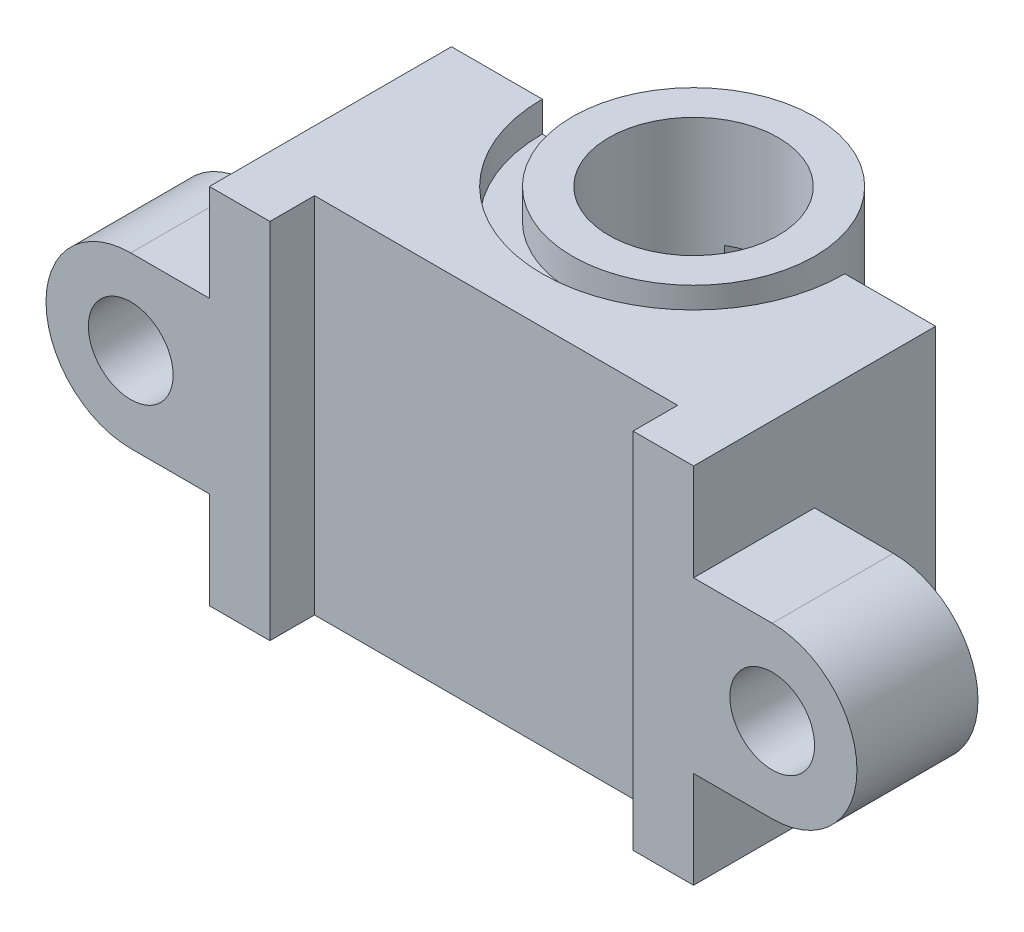
SolidWorks part; units mm, degrees
ref_plane "Front Plane" through (0, 0, 0) normal (0, 0, 1) x (1, 0, 0)
ref_plane "Top Plane" through (0, 0, 0) normal (0, 1, 0) x (1, 0, 0)
ref_plane "Right Plane" through (0, 0, 0) normal (1, 0, 0) x (0, 0, -1)
sketch "Sketch1" plane through (0, 0, 0) normal (0, 0, 1) x (1, 0, 0)
  line L1 (-40, -30) -> (40, -30)
  line L2 (-40, -30) -> (-40, 30)
  line L3 (-40, 30) -> (40, 30)
  line L4 (40, -30) -> (40, 30)
  line L5 (-40, -30) -> (40, 30) construction
  line L6 (-40, 30) -> (40, -30) construction
  point P0 (0, 0)
  dimension "D1" = 80
  dimension "D2" = 60
extrude "Boss-Extrude1" add sketch "Sketch1" against normal blind 40
sketch "Sketch2" plane through (0, 30, 0) normal (0, 1, 0) x (1, 0, 0)
  line L0 (40, 0) -> (-40, 0) construction
  line L1 (-30, 0) -> (30, 0)
  line L2 (-30, 0) -> (-30, 7.3681)
  line L3 (-30, 7.3681) -> (30, 7.3681)
  line L4 (30, 0) -> (30, 7.3681)
  point P6 (0, 7.3681)
  dimension "D1" = 60
extrude "Cut-Extrude1" cut sketch "Sketch2" against normal through all
sketch "Sketch4" plane through (0, 0, 0) normal (0, 0, 1) x (1, 0, 0)
  line L0 (40, -30) -> (40, 30) construction
  line L10 (40, -14) -> (53, -14)
  line L11 (40, -14) -> (40, 14)
  line L12 (40, 14) -> (53, 14)
  arc A2 (53, -14) -> (53, 14) centre (53, 0) ccw
  point P6 (40, 0)
  dimension "D1" = 13
extrude "Boss-Extrude2" add sketch "Sketch4" against normal blind 20
sketch "Sketch5" plane through (0, 0, -20) normal (0, 0, -1) x (-1, 0, 0)
  circle A0 centre (-53, 0) radius 7
  dimension "D1" = 14
extrude "Cut-Extrude2" cut sketch "Sketch5" against normal through all
mirror "Mirror1" about plane through (0, 0, 0) normal (1, 0, 0) of "Boss-Extrude2", "Cut-Extrude2"
sketch "Sketch6" plane through (0, -30, 0) normal (0, -1, 0) x (1, 0, 0)
  line L0 (-40, -40) -> (40, -40) construction
  circle A0 centre (0, -40) radius 25
  dimension "D1" = 50
extrude "Cut-Extrude3" cut sketch "Sketch6" against normal blind 5
mirror "Mirror2" about plane through (0, 0, 0) normal (0, 1, 0) of "Cut-Extrude3"
sketch "Sketch7" plane through (0, -25, 0) normal (0, -1, 0) x (1, 0, 0)
  line L0 (-25, -40) -> (25, -40) construction
  circle A0 centre (0, -40) radius 20
  dimension "D1" = 40
extrude "Boss-Extrude3" add sketch "Sketch7" against normal through all
sketch "Sketch8" plane through (0, -25, 0) normal (0, -1, 0) x (1, 0, 0)
  circle A0 centre (0, -40) radius 14
  dimension "D1" = 28
extrude "Cut-Extrude4" cut sketch "Sketch8" against normal through all
ref_plane "Plane1" through (0, 0, -60) normal (0, 0, 1) x (1, 0, 0)
sketch "Sketch11" plane through (0, 0, -60) normal (0, 0, 1) x (1, 0, 0)
  line L15 (7, 12) -> (-7, 12)
  line L16 (7, 12) -> (7, -2)
  line L17 (7, -2) -> (-7, -2)
  line L18 (-7, 12) -> (-7, -2)
  line L19 (7, 12) -> (-7, -2) construction
  line L20 (7, -2) -> (-7, 12) construction
  line L25 (-20, -25) -> (20, -25) construction
  point P0 (0, 5)
  point P8 (0, 0)
  dimension "D1" = 14
  dimension "D2" = 14
  dimension "D3" = 23
extrude "Cut-Extrude5" cut sketch "Sketch11" along normal blind 10
